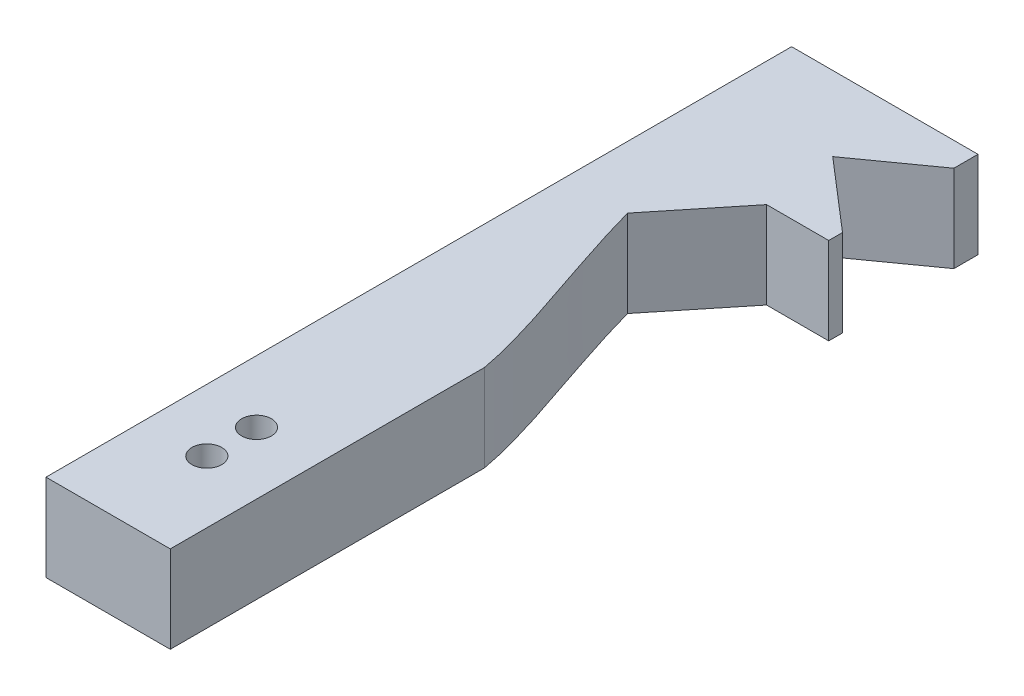
SolidWorks part; units mm, degrees
ref_plane "Front Plane" through (0, 0, 0) normal (0, 0, 1) x (1, 0, 0)
ref_plane "Top Plane" through (0, 0, 0) normal (0, 1, 0) x (1, 0, 0)
ref_plane "Right Plane" through (0, 0, 0) normal (1, 0, 0) x (0, 0, -1)
sketch "Sketch1" plane through (0, 0, 0) normal (0, 1, 0) x (1, 0, 0)
  line L0 (5, 30) -> (5, -9.5229)
  line L1 (-5, 30) -> (5, 30)
  line L2 (-5, 30) -> (-5, -30)
  line L3 (-5, -30) -> (5, -30)
  line L4 (5, 30) -> (5, -30)
  line L5 (-5, 30) -> (5, -30) construction
  line L6 (-5, -30) -> (5, 30) construction
  line L7 (5, 30) -> (5, 17.9871)
  line L8 (5, 17.9871) -> (0, 11.8027)
  line L9 (5, 30) -> (5, 17.9871)
  spline S0 degree 3 poles (5, 30) (-10.3529, 22.924) (7.6272, -0.4547) (5, -9.5229) knots 0 0 0 0 1 1 1 1
  point P0 (0, 0)
  dimension "D1" = 10
  dimension "D2" = 60
extrude "Boss-Extrude1" add sketch "Sketch1" along normal blind 7 contours L0 S0 L8 | S0 L1 L2 L3 L4 L0
sketch "Sketch2" plane through (5, 0, 0) normal (1, 0, 0) x (0, 0, -1)
  line L1 (17.9871, 7) -> (30, 7)
  line L2 (17.9871, 7) -> (17.9871, 0)
  line L3 (17.9871, 0) -> (30, 0)
  line L4 (30, 7) -> (30, 0)
extrude "Boss-Extrude3" add sketch "Sketch2" along normal blind 5
sketch "Sketch3" plane through (0, 7, 0) normal (0, 1, 0) x (1, 0, 0)
  line L0 (10, 28.0588) -> (4.3156, 23.9936)
  line L1 (10, 30) -> (10, 17.9871) construction
  line L2 (4.3156, 23.9936) -> (10, 19.0965)
  line L3 (10, 19.0965) -> (10, 28.0588)
extrude "Cut-Extrude1" cut sketch "Sketch3" against normal through all
sketch "Sketch4" plane through (0, 7, 0) normal (0, 1, 0) x (1, 0, 0)
  circle A0 centre (0, -22.0597) radius 1.2
  circle A1 centre (0, -18.0597) radius 1.2
  dimension "D1" = 2.4
  dimension "D2" = 2.4
  dimension "D3" = 4
extrude "Cut-Extrude2" cut sketch "Sketch4" against normal through all
